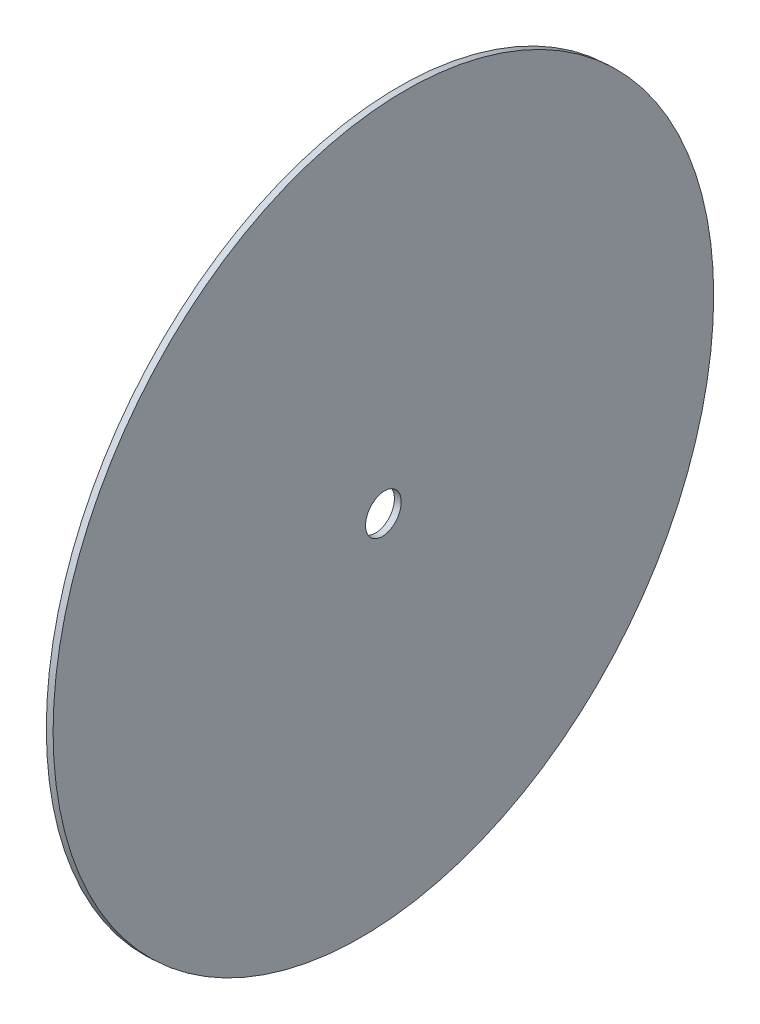
SolidWorks part; units mm, degrees
ref_plane "Plan de face" through (0, 0, 0) normal (0, 0, 1) x (1, 0, 0)
ref_plane "Plan de dessus" through (0, 0, 0) normal (0, 1, 0) x (1, 0, 0)
ref_plane "Plan de droite" through (0, 0, 0) normal (1, 0, 0) x (0, 0, -1)
ref_plane "Plan1" through (0, 72.3954, 0) normal (0, 1, 0) x (-1, 0, 0)
sketch "Esquisse1" plane through (0, 72.3954, 0) normal (0, 1, 0) x (-1, 0, 0)
  line L0 (-79.724, 224.4201) -> (-76.8974, 182.4151)
  line L1 (-76.8974, 182.4151) -> (-76.0993, 182.4688)
  line L2 (-76.0993, 182.4688) -> (-78.9258, 224.4738)
  line L3 (-78.9258, 224.4738) -> (-79.724, 224.4201)
  line L4 (-76.7327, 180.0207) -> (-75.9417, 180.0739) construction
  dimension "D1" = 4.8
  dimension "D2" = 89
  dimension "D3" = 0.8
revolve "Révolution1" add sketch "Esquisse1" angle 360 about L4
